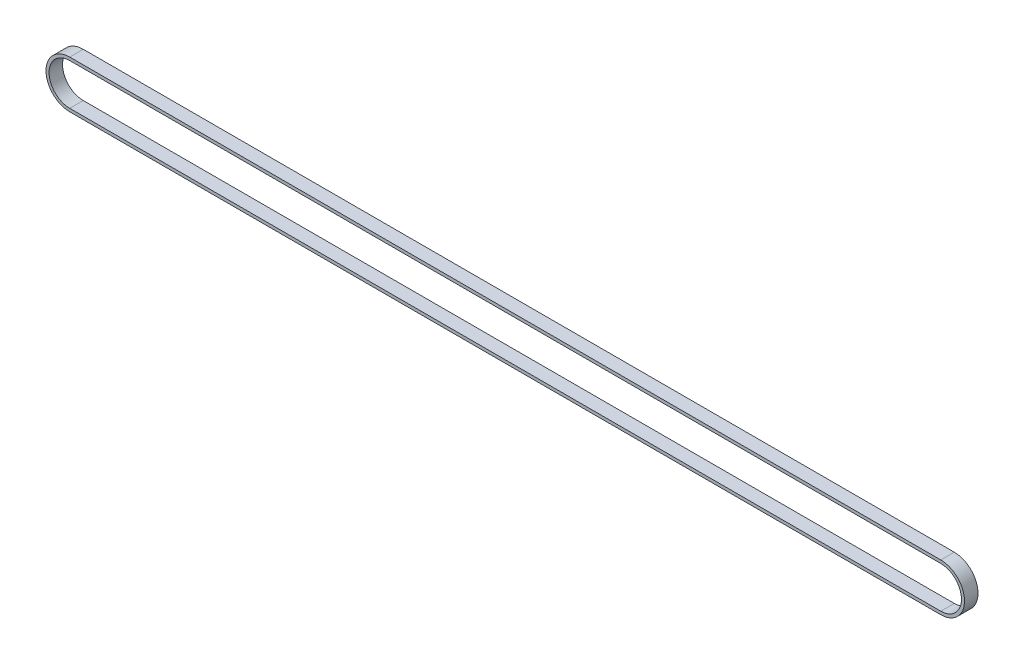
SolidWorks part; units mm, degrees
material "BUTYL"
ref_plane "Front Plane" through (0, 0, 0) normal (0, 0, 1) x (1, 0, 0)
ref_plane "Top Plane" through (0, 0, 0) normal (0, 1, 0) x (1, 0, 0)
ref_plane "Right Plane" through (0, 0, 0) normal (1, 0, 0) x (0, 0, -1)
sketch "Sketch1" plane through (0, 0, 0) normal (0, 0, 1) x (1, 0, 0)
  point P0 (0, 0)
  line B0 (193.5, 0) -> (-193.5, 0) construction
  circle B1 centre (-193.5, 0) radius 9.181 construction
  circle B2 centre (193.5, 0) radius 9.181 construction
sketch_block_instance "Block1-1"
sketch_block "Block1"
sketch "Sketch2" plane through (0, 0, 0) normal (0, 0, 1) x (1, 0, 0)
  line L0 (-193.5, 9.181) -> (193.5, 9.181)
  line L1 (-193.5, -9.181) -> (193.5, -9.181)
  line L2 (-193.5, 10.541) -> (193.5, 10.541)
  line L3 (-193.5, -10.541) -> (193.5, -10.541)
  arc A0 (-193.5, 9.181) -> (-193.5, -9.181) centre (-193.5, 0) ccw
  arc A1 (193.5, -9.181) -> (193.5, 9.181) centre (193.5, 0) ccw
  circle A2 centre (193.5, 0) radius 9.181 construction
  circle A3 centre (-193.5, 0) radius 9.181 construction
  arc A4 (193.5, -10.541) -> (193.5, 10.541) centre (193.5, 0) ccw
  arc A5 (-193.5, 10.541) -> (-193.5, -10.541) centre (-193.5, 0) ccw
  dimension "D1" = 1.36
extrude "Boss-Extrude1" add sketch "Sketch2" along normal mid plane 6
